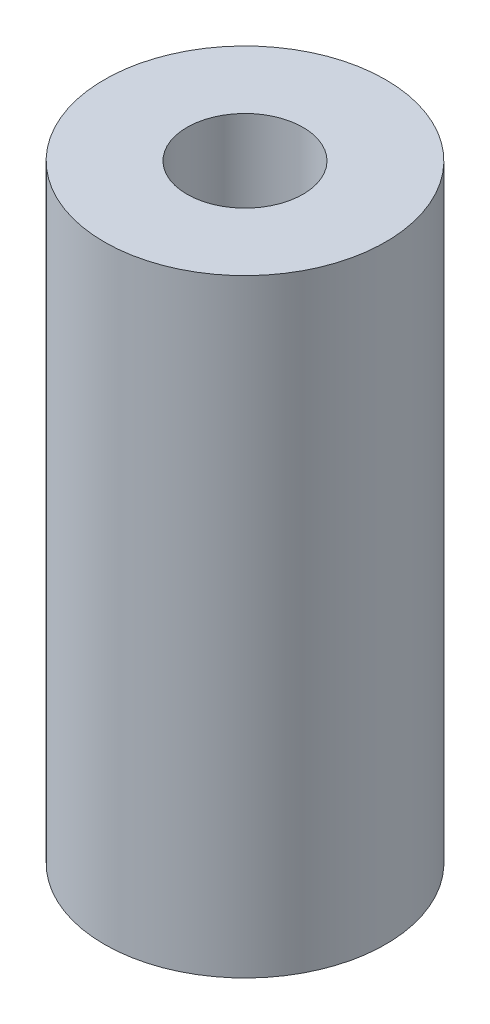
SolidWorks part; units mm, degrees
material "5052-H34"
ref_plane "正面" through (0, 0, 0) normal (0, 0, 1) x (1, 0, 0)
ref_plane "平面" through (0, 0, 0) normal (0, 1, 0) x (1, 0, 0)
ref_plane "右側面" through (0, 0, 0) normal (1, 0, 0) x (0, 0, -1)
sketch "ｽｹｯﾁ1" plane through (0, 0, 0) normal (0, 1, 0) x (1, 0, 0)
  circle A0 centre (0, 0) radius 1.65
  circle A1 centre (0, 0) radius 4
  dimension "D1" = 3.3
  dimension "D2" = 8
extrude "ﾎﾞｽ - 押し出し1" add sketch "ｽｹｯﾁ1" along normal blind 17.3
